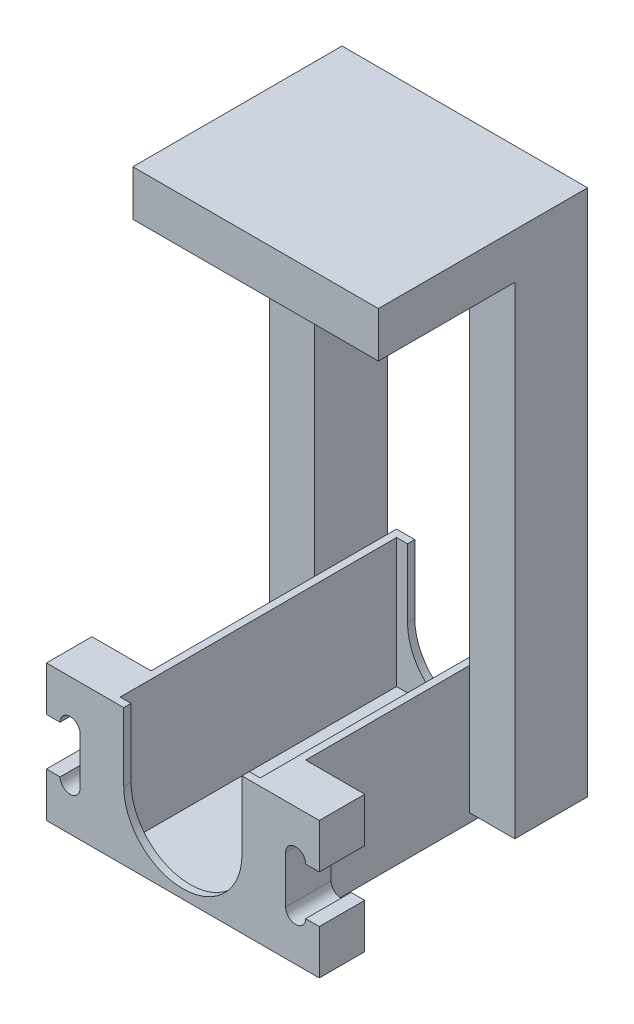
SolidWorks part; units mm, degrees
ref_plane "Alzado" through (0, 0, 0) normal (0, 0, 1) x (1, 0, 0)
ref_plane "Planta" through (0, 0, 0) normal (0, 1, 0) x (1, 0, 0)
ref_plane "Vista lateral" through (0, 0, 0) normal (1, 0, 0) x (0, 0, -1)
sketch "Croquis1" plane through (0, 0, 0) normal (0, 0, 1) x (1, 0, 0)
  line L1 (-8.5, 7.5) -> (8.5, 7.5)
  line L2 (-8.5, 7.5) -> (-8.5, -7.5)
  line L3 (-8.5, -7.5) -> (8.5, -7.5)
  line L4 (8.5, 7.5) -> (8.5, -7.5)
  line L5 (-8.5, 7.5) -> (8.5, -7.5) construction
  line L6 (-8.5, -7.5) -> (8.5, 7.5) construction
  point P0 (0, 0)
  dimension "D1" = 17
  dimension "D2" = 15
extrude "Saliente-Extruir1" add sketch "Croquis1" along normal blind 32
shell "Vaciado1" thickness 0.8
sketch "Croquis2" plane through (0, 0, 32) normal (0, 0, 1) x (1, 0, 0)
  line L0 (-8.5, 7.5) -> (-7.5, 7.5) construction
  line L1 (-8.5, -7.5) -> (-8.5, -6.5) construction
  line L2 (8.5, 7.5) -> (7.5, 7.5) construction
  line L3 (-7.5, 7.5) -> (-7.5, -6.5) construction
  line L4 (-7.5, -6.5) -> (7.5, -6.5) construction
  line L5 (7.5, -6.5) -> (7.5, 7.5) construction
  line L6 (-6.5, 0) -> (-6.5, 7.5)
  line L7 (8.5, 7.5) -> (-8.5, 7.5) construction
  line L8 (-6.5, 7.5) -> (6.5, 7.5)
  line L9 (6.5, 7.5) -> (6.5, 0)
  arc A0 (-6.5, 0) -> (6.5, 0) centre (0, 0) ccw
  dimension "D1" = 1
  dimension "D2" = 1
  dimension "D3" = 1
extrude "Cortar-Extruir1" cut sketch "Croquis2" against normal blind 32
sketch "Croquis3" plane through (8.5, 0, 0) normal (1, 0, 0) x (0, 0, -1)
  line L0 (-32, -7.5) -> (0, -7.5) construction
  line L1 (-32, 7.5) -> (-27, 7.5)
  line L2 (-32, 7.5) -> (-32, -7.5)
  line L3 (-32, -7.5) -> (-27, -7.5)
  line L4 (-27, 7.5) -> (-27, -7.5)
  dimension "D1" = 5
extrude "Saliente-Extruir2" add sketch "Croquis3" along normal blind 6.5
sketch "Croquis4" plane through (-8.5, 0, 0) normal (-1, 0, 0) x (0, 0, 1)
  line L0 (32, -7.5) -> (0, -7.5) construction
  line L1 (32, 7.5) -> (27, 7.5)
  line L2 (32, 7.5) -> (32, -7.5)
  line L3 (32, -7.5) -> (27, -7.5)
  line L4 (27, 7.5) -> (27, -7.5)
  dimension "D1" = 5
extrude "Saliente-Extruir3" add sketch "Croquis4" along normal blind 6.5
sketch "Croquis5" plane through (0, 0, 32) normal (0, 0, 1) x (1, 0, 0)
  line L0 (-11.3, 0) -> (11.3, 0)
  line L1 (-11.3, 2.6) -> (-11.3, -2.6)
  line L2 (11.3, 2.6) -> (11.3, -2.6)
  line L5 (-11.3, 2.6) -> (-11.3, -2.6)
  line L7 (-13.5, 2.6) -> (-13.5, -2.6)
  line L9 (11.3, 2.6) -> (11.3, -2.6)
  line L11 (13.5, 2.6) -> (13.5, -2.6)
  arc A0 (-11.3, 2.6) -> (-13.5, 2.6) centre (-12.4, 2.6) ccw
  arc A1 (-13.5, -2.6) -> (-11.3, -2.6) centre (-12.4, -2.6) ccw
  arc A2 (13.5, 2.6) -> (11.3, 2.6) centre (12.4, 2.6) ccw
  arc A3 (11.3, -2.6) -> (13.5, -2.6) centre (12.4, -2.6) ccw
  point P4 (0, 0)
  point P8 (-11.3, 0)
  point P10 (11.3, 0)
  dimension "D1" = 22.6
  dimension "D2" = 5.2
  dimension "D3" = 5.2
  dimension "D4" = 2.2
  dimension "D5" = 2.2
extrude "Cortar-Extruir2" cut sketch "Croquis5" against normal blind 6.5 contours L7 A1 L1 A0 | L2 A3 L11 A2
sketch "Croquis6" plane through (0, 0, 32) normal (0, 0, 1) x (1, 0, 0)
  line L0 (-15, -7.5) -> (-15, 7.5) construction
  line L1 (-13.5, 2.6) -> (-15, 2.6)
  line L2 (-13.5, 2.6) -> (-13.5, -2.6)
  line L3 (-13.5, -2.6) -> (-15, -2.6)
  line L4 (-15, 2.6) -> (-15, -2.6)
  line L5 (15, 7.5) -> (15, -7.5) construction
  line L6 (13.5, 2.6) -> (15, 2.6)
  line L7 (13.5, 2.6) -> (13.5, -2.6)
  line L8 (13.5, -2.6) -> (15, -2.6)
  line L9 (15, 2.6) -> (15, -2.6)
extrude "Cortar-Extruir3" cut sketch "Croquis6" against normal blind 10
sketch "Croquis7" plane through (8.5, 0, 0) normal (1, 0, 0) x (0, 0, -1)
  line L0 (0, 6.5) -> (0, -6.5)
  line L1 (0, 6.5) -> (-1, 6.5) construction
  line L3 (-1, 6.5) -> (-9, 6.5)
  line L4 (-1, 6.5) -> (-1, -6.5)
  line L5 (-1, -6.5) -> (-9, -6.5)
  line L6 (-9, 6.5) -> (-9, -6.5)
  point P4 (0, 0)
  dimension "D1" = 13
  dimension "D2" = 1
  dimension "D3" = 8
extrude "Saliente-Extruir4" add sketch "Croquis7" along normal blind 5 contours L3 L6 L5 L4
sketch "Croquis8" plane through (-8.5, 0, 0) normal (-1, 0, 0) x (0, 0, 1)
  line L0 (0, -6.5) -> (0, 6.5)
  line L2 (0, 6.5) -> (1, 6.5) construction
  line L4 (1, 6.5) -> (9, 6.5)
  line L5 (1, 6.5) -> (1, -6.5)
  line L6 (1, -6.5) -> (9, -6.5)
  line L7 (9, 6.5) -> (9, -6.5)
  point P4 (0, 0)
  dimension "D1" = 13
  dimension "D2" = 1
  dimension "D3" = 8
extrude "Saliente-Extruir5" add sketch "Croquis8" along normal blind 5 contours L7 L4 L5 L6
sketch "Croquis9" plane through (0, 6.5, 0) normal (0, 1, 0) x (1, 0, 0)
  line L1 (-13.5, -1) -> (-8.5, -1)
  line L2 (-13.5, -1) -> (-13.5, -9)
  line L3 (-13.5, -9) -> (-8.5, -9)
  line L4 (-8.5, -1) -> (-8.5, -9)
  line L5 (8.5, -9) -> (13.5, -9)
  line L6 (8.5, -9) -> (8.5, -1)
  line L7 (8.5, -1) -> (13.5, -1)
  line L8 (13.5, -9) -> (13.5, -1)
extrude "Saliente-Extruir6" add sketch "Croquis9" along normal blind 45
sketch "Croquis10" plane through (0, 0, 9) normal (0, 0, 1) x (1, 0, 0)
  line L0 (-8.5, 51.5) -> (-8.5, 7.5) construction
  line L1 (-13.5, 51.5) -> (-8.5, 51.5)
  line L2 (-13.5, 51.5) -> (-13.5, 46.5)
  line L3 (-13.5, 46.5) -> (-8.5, 46.5)
  line L4 (-8.5, 51.5) -> (-8.5, 46.5)
  line L5 (13.5, 51.5) -> (13.5, -6.5) construction
  line L6 (8.5, 51.5) -> (13.5, 51.5)
  line L7 (8.5, 51.5) -> (8.5, 46.5)
  line L8 (8.5, 46.5) -> (13.5, 46.5)
  line L9 (13.5, 51.5) -> (13.5, 46.5)
  dimension "D1" = 5
  dimension "D2" = 5
extrude "Saliente-Extruir7" add sketch "Croquis10" along normal blind 15
sketch "Croquis11" plane through (-8.5, 0, 0) normal (1, 0, 0) x (0, 0, -1)
  line L0 (-1, 51.5) -> (-1, 7.5) construction
  line L1 (-24, 51.5) -> (-1, 51.5)
  line L2 (-24, 51.5) -> (-24, 46.5)
  line L3 (-24, 46.5) -> (-1, 46.5)
  line L4 (-1, 51.5) -> (-1, 46.5)
extrude "Saliente-Extruir8" add sketch "Croquis11" along normal blind 11.5
sketch "Croquis12" plane through (8.5, 0, 0) normal (-1, 0, 0) x (0, 0, 1)
  line L1 (1, 51.5) -> (24, 51.5)
  line L2 (1, 51.5) -> (1, 46.5)
  line L3 (1, 46.5) -> (24, 46.5)
  line L4 (24, 51.5) -> (24, 46.5)
extrude "Saliente-Extruir9" add sketch "Croquis12" along normal blind 11.5
